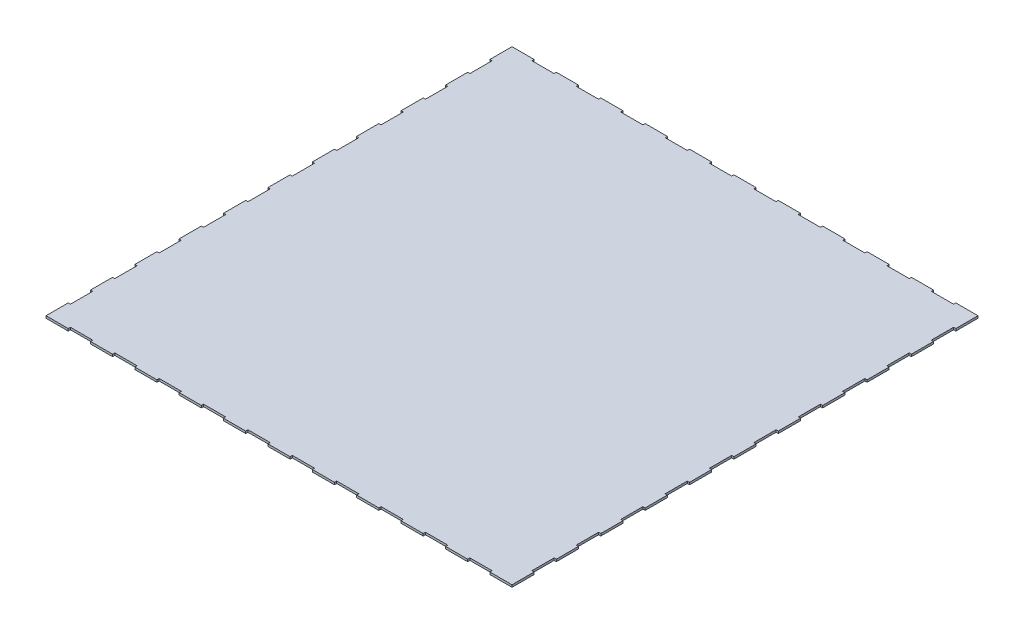
SolidWorks part; units mm, degrees
ref_plane "Front Plane" through (0, 0, 0) normal (0, 0, 1) x (1, 0, 0)
ref_plane "Top Plane" through (0, 0, 0) normal (0, 1, 0) x (1, 0, 0)
ref_plane "Right Plane" through (0, 0, 0) normal (1, 0, 0) x (0, 0, -1)
sketch "Sketch1" plane through (0, 0, 0) normal (0, 1, 0) x (1, 0, 0)
  line L1 (-315, -315) -> (315, -315)
  line L2 (-315, -315) -> (-315, 315)
  line L3 (-315, 315) -> (315, 315)
  line L4 (315, -315) -> (315, 315)
  line L5 (0, 315) -> (0, -315) construction
  line L6 (-315, 0) -> (315, 0) construction
  point P0 (0, 0)
extrude "Boss-Extrude1" add sketch "Sketch1" along normal blind 3
ref_plane "Plane1" through (0, 0, 285) normal (0, 0, 1) x (1, 0, 0)
sketch "Sketch3" plane through (0, 3, 0) normal (0, 1, 0) x (1, 0, 0)
  line L0 (-315, 315) -> (-315, -315) construction
  line L1 (-315, -285.0068) -> (-312, -285.0068)
  line L2 (-315, -285.0068) -> (-315, -255.0068)
  line L3 (-315, -255.0068) -> (-312, -255.0068)
  line L4 (-312, -285.0068) -> (-312, -255.0068)
  dimension "D1" = 30
  dimension "D2" = 3
extrude "Cut-Extrude2" cut sketch "Sketch3" against normal blind 3
pattern_linear "LPattern2" count 10 spacing 60 along (0, 0, -1) of "Cut-Extrude2"
ref_plane "Plane2" through (0, 0, 0) normal (1, 0, 0) x (0, 0, -1)
mirror "Mirror1" about plane through (0, 0, 0) normal (1, 0, 0) of "LPattern2", "Cut-Extrude2"
ref_plane "Plane3" through (-285, 0, 0) normal (-1, 0, 0) x (0, 0, 1)
sketch "Sketch5" plane through (0, 3, 0) normal (0, 1, 0) x (1, 0, 0)
  line L0 (-315, -315) -> (315, -315) construction
  line L1 (-285.0003, -315) -> (-255.0003, -315)
  line L2 (-285.0003, -315) -> (-285.0003, -312)
  line L3 (-285.0003, -312) -> (-255.0003, -312)
  line L4 (-255.0003, -315) -> (-255.0003, -312)
  dimension "D1" = 30
  dimension "D2" = 3
extrude "Cut-Extrude3" cut sketch "Sketch5" against normal blind 3
pattern_linear "LPattern3" count 10 spacing 60 along (1, 0, 0) of "Cut-Extrude3"
ref_plane "Plane4" through (0, 0, 0) normal (0, 0, 1) x (1, 0, 0)
mirror "Mirror2" about plane through (0, 0, 0) normal (0, 0, 1) of "LPattern3", "Cut-Extrude3"
other "SurfaceCut1" [suppressed]
other "SurfaceCut2" [suppressed]
